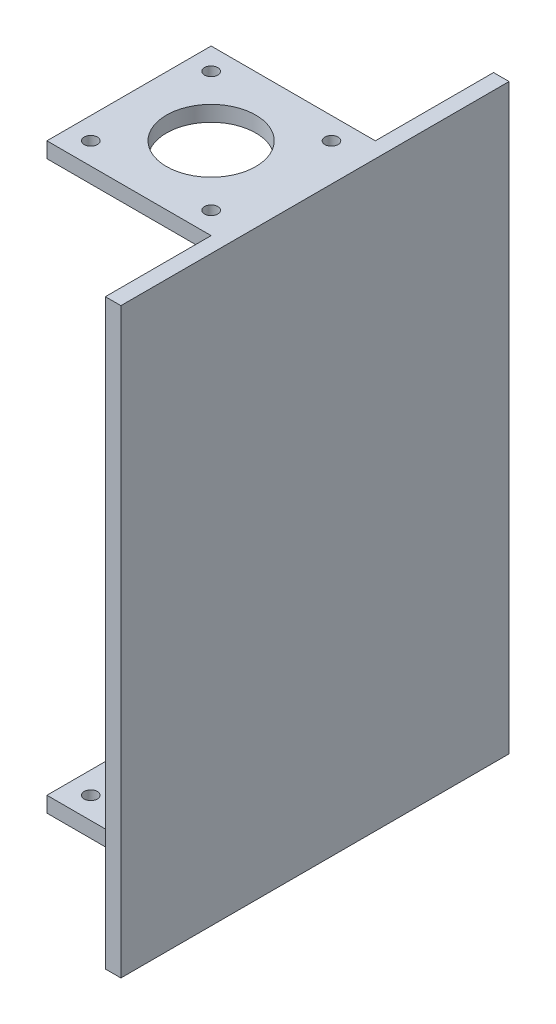
SolidWorks part; units mm, degrees
ref_plane "Front Plane" through (0, 0, 0) normal (0, 0, 1) x (1, 0, 0)
ref_plane "Top Plane" through (0, 0, 0) normal (0, 1, 0) x (1, 0, 0)
ref_plane "Right Plane" through (0, 0, 0) normal (1, 0, 0) x (0, 0, -1)
sketch "Sketch2" plane through (0, 0, 0) normal (0, 1, 0) x (1, 0, 0)
  line L1 (-21.15, -21.15) -> (21.15, -21.15)
  line L2 (-21.15, -21.15) -> (-21.15, 21.15)
  line L3 (-21.15, 21.15) -> (21.15, 21.15)
  line L4 (21.15, -21.15) -> (21.15, 21.15)
  line L5 (-21.15, -21.15) -> (21.15, 21.15) construction
  line L6 (-21.15, 21.15) -> (21.15, -21.15) construction
  circle A0 centre (-15.5, 15.5) radius 1.7
  circle A1 centre (15.5, 15.5) radius 1.7
  circle A2 centre (15.5, -15.5) radius 1.7
  circle A3 centre (-15.5, -15.5) radius 1.7
  circle A4 centre (0, 0) radius 11.5
  point P0 (0, 0)
  dimension "D4" = 3.4
  dimension "D5" = 23
  dimension "D1" = 42.3
  dimension "D2" = 42.3
  dimension "D3" = 31
extrude "Boss-Extrude1" add sketch "Sketch2" along normal blind 4
ref_plane "Plane1" through (-21.15, 0, -21.15) normal (-1, 0, 0) x (0, 0, 1)
sketch "Sketch6" plane through (0, 0, -21.15) normal (0, 0, -1) x (-1, 0, 0)
  line L0 (0, 0) -> (28.2537, 0) construction
ref_plane "Plane3" through (-21.15, 4, -21.15) normal (-1, 0, 0) x (0, 0, 1)
ref_plane "Plane4" through (-21.15, 4, -21.15) normal (0, 0, 1) x (1, 0, 0)
ref_plane "Plane5" through (21.15, 4, 21.15) normal (1, 0, 0) x (0, 0, -1)
sketch "Sketch10" plane through (21.15, 4, 21.15) normal (1, 0, 0) x (0, 0, -1)
  line L0 (0, 0) -> (-9.5873, 0) construction
  line L1 (-27.2441, 0) -> (72.7559, 0)
  line L2 (72.7559, 0) -> (72.7559, -150)
  line L3 (-27.2441, 0) -> (-27.2441, -150)
  line L4 (-27.2441, -150) -> (72.7559, -150)
  dimension "D1" = 100
  dimension "D2" = 150
extrude "Boss-Extrude3" add sketch "Sketch10" along normal blind 4
ref_plane "Plane6" through (0, -71, 0) normal (0, -1, 0) x (-1, 0, 0)
mirror "Mirror1" about plane through (0, -71, 0) normal (0, -1, 0) of "Boss-Extrude1"
